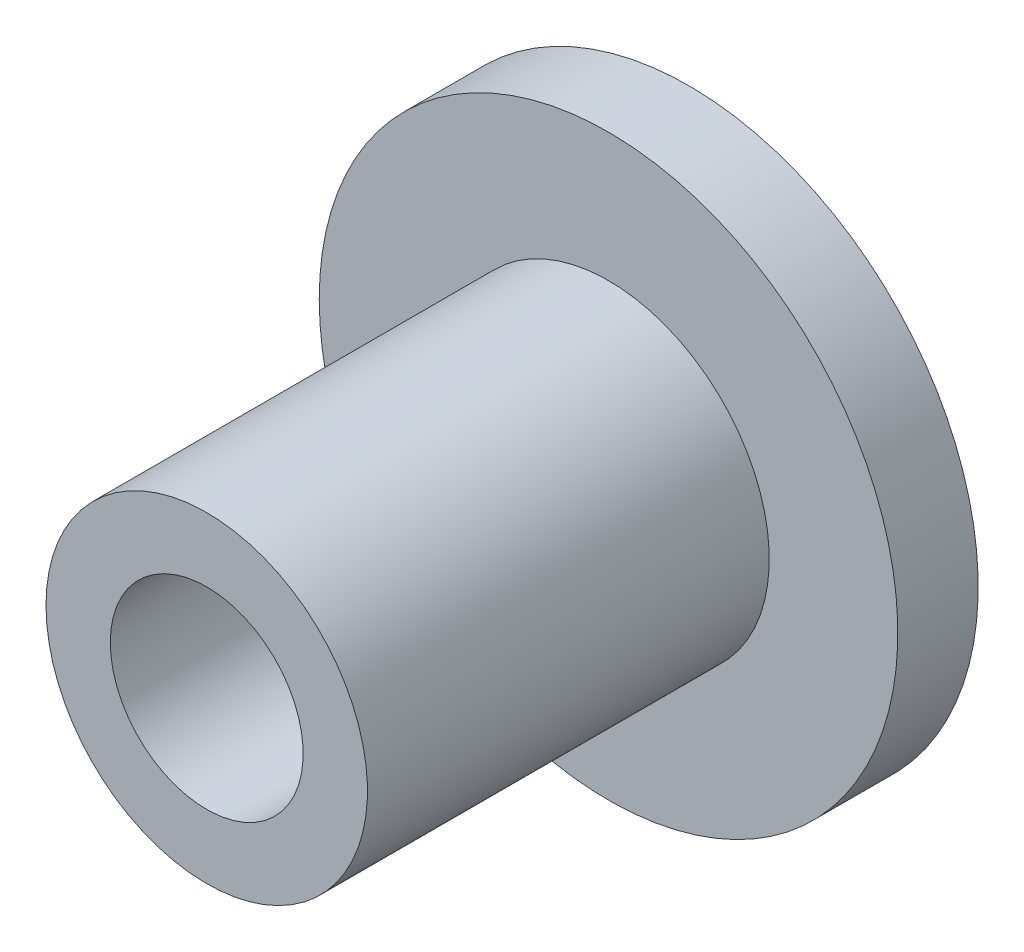
SolidWorks part; units mm, degrees
ref_plane "前视基准面" through (0, 0, 0) normal (0, 0, 1) x (1, 0, 0)
ref_plane "上视基准面" through (0, 0, 0) normal (0, 1, 0) x (1, 0, 0)
ref_plane "右视基准面" through (0, 0, 0) normal (1, 0, 0) x (0, 0, -1)
sketch "草图1" plane through (0, 0, 0) normal (0, 1, 0) x (1, 0, 0)
  line L0 (0, 0) -> (0, -30) construction
  line L1 (6, 0) -> (18, 0)
  line L2 (18, 0) -> (18, -5)
  line L3 (18, -5) -> (10, -5)
  line L4 (10, -5) -> (10, -30)
  line L5 (10, -30) -> (6, -30)
  line L6 (6, -30) -> (6, 0)
revolve "旋转1" add sketch "草图1" angle 360 about L0
